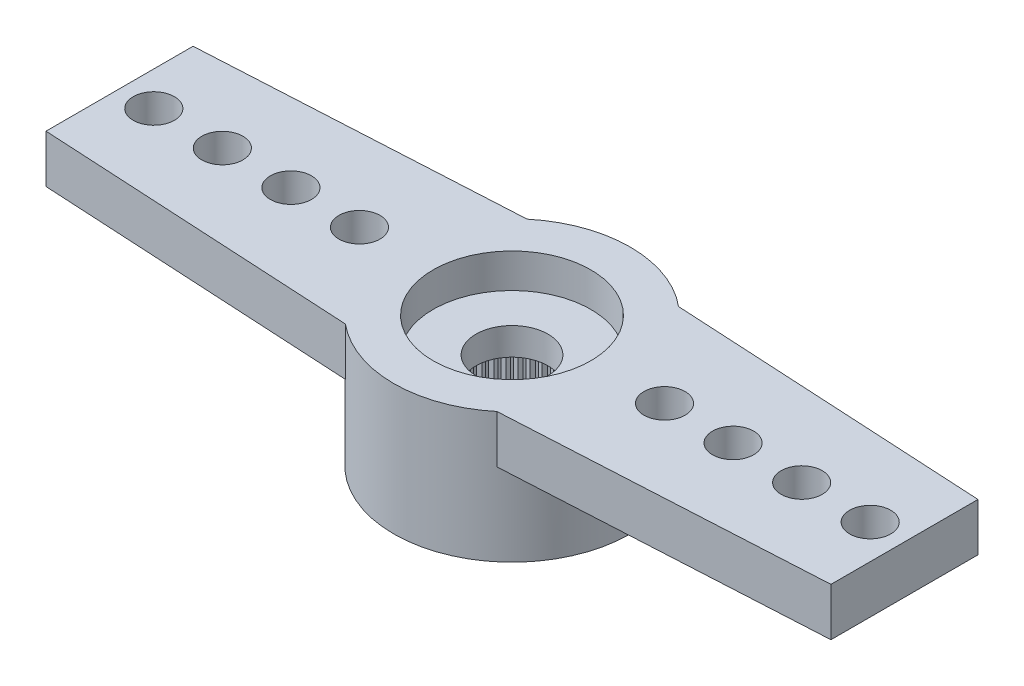
SolidWorks part; units mm, degrees
material "PVC Rígido"
ref_plane "Plano frontal" through (0, 0, 0) normal (0, 0, 1) x (1, 0, 0)
ref_plane "Plano superior" through (0, 0, 0) normal (0, 1, 0) x (1, 0, 0)
ref_plane "Plano direito" through (0, 0, 0) normal (1, 0, 0) x (0, 0, -1)
sketch "Esboço1" plane through (0, 0, 0) normal (0, 1, 0) x (1, 0, 0)
  line L0 (0, 0) -> (-14.05, 0) construction
  line L1 (-14.1591, 1.997) -> (-2.2091, 2.65)
  line L2 (-2.2091, -2.65) -> (-14.1591, -1.997)
  arc A0 (-2.2091, -2.65) -> (-2.2091, 2.65) centre (0, 0) ccw
  arc A1 (-14.1591, 1.997) -> (-14.1591, -1.997) centre (-14.05, 0) ccw
  dimension "D1" = 6.9
  dimension "D2" = 4
  dimension "D3" = 19.5
  dimension "D4" = 5.3
extrude "Ressalto-extrusão1" add sketch "Esboço1" against normal blind 1.4
sketch "Esboço2" plane through (0, -1.4, 0) normal (0, -1, 0) x (1, 0, 0)
  arc A0 (-2.2091, -2.65) -> (-2.2091, 2.65) centre (0, 0) ccw construction
  circle A1 centre (0, 0) radius 3.45
extrude "Ressalto-extrusão2" add sketch "Esboço2" along normal offset from surface (2.4 mm away) 3.8 up to face at (-7.242, 0, 0)
hole_wizard "Furo4" positions "Esboço9" profile "Esboço10" legacy end condition through all
sketch "Esboço9" plane through (0, 0, 0) normal (0, 1, 0) x (1, 0, 0)
  line L1 (-14.45, 0) -> (0, 0) construction
  arc A2 (-14.1591, 1.997) -> (-14.1591, -1.997) centre (-14.05, 0) ccw construction
  point P0 (-14.45, 0)
  point P19 (-16.05, 0)
  dimension "D1" = 1.6
sketch "Esboço10" plane through (-14.45, 0, 0) normal (1, 0, 0) x (0, 0, 1)
  line L0 (0, 0) -> (0, 3.8)
  line L1 (0, 3.8) -> (0.6, 3.8)
  line L2 (0.6, 3.8) -> (0.6, 0)
  line L3 (0.6, 0) -> (0, 0)
  line L4 (0, 110) -> (0, -10) construction
  dimension "Diameter" = 1.2
  dimension "Depth" = 3.8
pattern_linear "Padrão linear1" count 6 spacing 2 along (1, 0, 0) of "Furo4"
pattern_circular "PadrãoCircular2" count 2 over 360 about axis through (0, 0, 0) along (0, 1, 0) of "Ressalto-extrusão1", "Furo4", "Padrão linear1"
hole_wizard "Furo1" positions "Esboço3" profile "Esboço4" legacy
sketch "Esboço3" plane through (0, -3.8, 0) normal (0, -1, 0) x (-1, 0, 0)
  point P0 (0, 0)
sketch "Esboço4" plane through (0, -3.8, 0) normal (1, 0, 0) x (0, 0, -1)
  line L0 (0, 0) -> (0, 2)
  line L1 (0, 2) -> (2.475, 2)
  line L2 (2.475, 2) -> (2.475, 0)
  line L3 (2.475, 0) -> (0, 0)
  line L4 (0, 110) -> (0, -10) construction
  dimension "Diameter" = 4.95
  dimension "Depth" = 2
hole_wizard "Furo2" positions "Esboço5" profile "Esboço6" legacy
sketch "Esboço5" plane through (0, 0, 0) normal (0, 1, 0) x (1, 0, 0)
  point P0 (0, 0)
sketch "Esboço6" plane through (0, 0, 0) normal (1, 0, 0) x (0, 0, 1)
  line L0 (0, 0) -> (0, 1)
  line L1 (0, 1) -> (2.3, 1)
  line L2 (2.3, 1) -> (2.3, 0)
  line L3 (2.3, 0) -> (0, 0)
  line L4 (0, 110) -> (0, -10) construction
  dimension "Diameter" = 4.6
  dimension "Depth" = 1
hole_wizard "Furo3" positions "Esboço7" profile "Esboço8" legacy end condition through all
sketch "Esboço7" plane through (0, 0, 0) normal (0, 1, 0) x (1, 0, 0)
  point P0 (0, 0)
sketch "Esboço8" plane through (0, 0, 0) normal (1, 0, 0) x (0, 0, 1)
  line L0 (0, 0) -> (0, 3.8)
  line L1 (0, 3.8) -> (1.05, 3.8)
  line L2 (1.05, 3.8) -> (1.05, 0)
  line L3 (1.05, 0) -> (0, 0)
  line L4 (0, 110) -> (0, -10) construction
  dimension "Diameter" = 2.1
  dimension "Depth" = 3.8
sketch "Esboço11" plane through (0, -3.8, 0) normal (0, -1, 0) x (1, 0, 0)
  line L0 (-0.0981, 2.4731) -> (0, 2.375)
  line L1 (0, 2.375) -> (0.0981, 2.4731)
  line L2 (0, 0) -> (0, 2.475) construction
  circle A0 centre (0, 0) radius 2.375 construction
  circle A1 centre (0, 0) radius 2.475
  arc A2 (0.0981, 2.4731) -> (-0.0981, 2.4731) centre (0, 0) ccw
  dimension "D3" = 4.75
  dimension "D2" = 0.1
  dimension "D1" = 0
extrude "Ressalto-extrusão3" add sketch "Esboço11" against normal up to surface (2 mm away) up to face at (0, -1.8, 1.05)
pattern_circular "PadrãoCircular1" count 60 over 360 about axis through (0, 0, 0) along (0, 1, 0) of "Ressalto-extrusão3"
ref_plane "Plane1" through (-5.3014, 0, 5.5681) normal (0.6896, 0, -0.7242) x (0, 1, 0)
sketch "Sketch1" plane through (-5.3014, 0, 5.5681) normal (0.6896, 0, -0.7242) x (0, 1, 0)
  line L0 (0, 3.45) -> (-3.8, 3.45) construction
  line L1 (2.7161, -3.9543) -> (-3.1035, -3.9543)
  line L2 (2.7161, -3.9543) -> (2.7161, 3.45)
  line L3 (2.7161, 3.45) -> (-3.1035, 3.45)
  line L4 (-3.1035, -3.9543) -> (-3.1035, 3.45)
sketch "Sketch2" plane through (0, 0, 0) normal (0, 1, 0) x (1, 0, 0)
  line L0 (16.05, 0) -> (-16.05, 0)
  line L1 (-11.45, -2.1451) -> (-11.45, 2.1451)
  line L2 (-14.1591, -1.997) -> (-2.2091, -2.65) construction
  line L3 (-2.2091, 2.65) -> (-14.1591, 1.997) construction
  line L4 (0, 0) -> (0, 3.45)
  line L5 (11.45, -2.1451) -> (11.45, 2.1451)
  line L6 (-11.45, -2.1451) -> (-18.0748, -1.7831)
  line L7 (-18.0748, -1.7831) -> (-17.5014, 2.1451)
  line L8 (-17.5014, 2.1451) -> (-11.45, 2.1451)
  line L9 (11.45, -2.1451) -> (17.0395, -2.1451)
  line L10 (17.0395, -2.1451) -> (15.7214, 1.9429)
  line L11 (15.7214, 1.9429) -> (11.45, 2.1451)
  arc A0 (-14.1591, 1.997) -> (-14.1591, -1.997) centre (-14.05, 0) ccw construction
  circle A1 centre (-10.45, 0) radius 0.6 construction
  arc A2 (2.2091, 2.65) -> (-2.2091, 2.65) centre (0, 0) ccw construction
  spline S0 degree 3 poles (15.8563, 1.7298) (16.0716, 1.5248) (16.2539, 1.4345) (16.5085, 1.401) (16.5902, 1.4063) (16.7348, 1.4491) (16.7968, 1.486) (16.8931, 1.5875) (16.926, 1.6505) (16.9584, 1.7939) (16.9576, 1.874) (16.9052, 2.1202) (16.8011, 2.2948) (16.5884, 2.4973) (16.5082, 2.5555) (16.3412, 2.6437) (16.2556, 2.6734) (16.0879, 2.7003) (16.0088, 2.6969) (15.8673, 2.6572) (15.8057, 2.6206) (15.6627, 2.4702) (15.6242, 2.3121) (15.6703, 2.0595) (15.7024, 1.9726) (15.7958, 1.8073) (15.8563, 1.7298) (16.0716, 1.5248) (16.2539, 1.4345) knots -0.0625 -0.0625 0 0 0.125 0.125 0.1875 0.1875 0.25 0.25 0.3125 0.3125 0.375 0.375 0.5 0.5 0.5625 0.5625 0.625 0.625 0.6875 0.6875 0.75 0.75 0.875 0.875 0.9375 0.9375 1 1 1.125 1.125 1.1875 only from (15.9281, 1.6615) to (15.9281, 1.6615) construction
  circle M9 centre (12.45, 0) radius 0.6
  circle M10 centre (14.45, 0) radius 0.6
  line M11 (-14.1591, -1.997) -> (-2.2091, -2.65)
  line M13 (2.2091, -2.65) -> (14.1591, -1.997)
  arc M14 (14.1591, -1.997) -> (14.1591, 1.997) centre (14.05, 0) ccw
  line M15 (14.1591, 1.997) -> (2.2091, 2.65)
  line M17 (-2.2091, 2.65) -> (-14.1591, 1.997)
  arc M18 (-14.1591, 1.997) -> (-14.1591, -1.997) centre (-14.05, 0) ccw
  circle M19 centre (-12.45, 0) radius 0.6
  circle M20 centre (-14.45, 0) radius 0.6
  dimension "D1" = 90
  dimension "D2" = 1
extrude "Cut-Extrude2" cut sketch "Sketch2" against normal blind 10 contours L5 L0 M13 M14 M10 M9 | L8 L7 L6 M18 M17 | L0 L1 M17 M18 M20 M19 | L1 L0 M11 M19 M20 M18 | L5 L0 M9 M10 M14 M15
